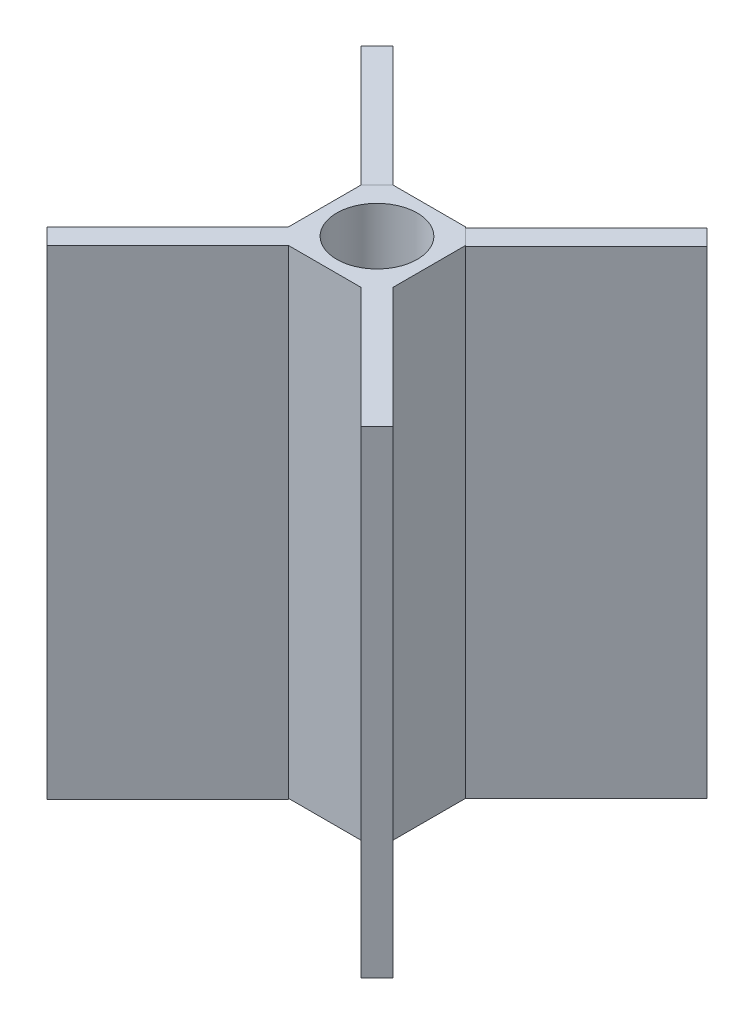
SolidWorks part; units mm, degrees
ref_plane "Front Plane" through (0, 0, 0) normal (0, 0, 1) x (1, 0, 0)
ref_plane "Top Plane" through (0, 0, 0) normal (0, 1, 0) x (1, 0, 0)
ref_plane "Right Plane" through (0, 0, 0) normal (1, 0, 0) x (0, 0, -1)
sketch "Sketch1" plane through (0, 0, 0) normal (0, 1, 0) x (1, 0, 0)
  line L1 (-6.5, -6.5) -> (6.5, -6.5)
  line L2 (-6.5, -6.5) -> (-6.5, 6.5)
  line L3 (-6.5, 6.5) -> (6.5, 6.5)
  line L4 (6.5, -6.5) -> (6.5, 6.5)
  line L5 (-6.5, -6.5) -> (6.5, 6.5) construction
  line L6 (-6.5, 6.5) -> (6.5, -6.5) construction
  point P0 (0, 0)
  dimension "D1" = 13
  dimension "D2" = 13
extrude "Boss-Extrude1" add sketch "Sketch1" along normal blind 59.5
chamfer "Chamfer1" distance 2 angle 45 4 edges at (-6.5, 29.75, 6.5) (6.5, 29.75, 6.5) (6.5, 29.75, -6.5) (-6.5, 29.75, -6.5)
sketch "Sketch6" plane through (5.5, 0, -5.5) normal (0.7071, 0, -0.7071) x (-0.7071, 0, -0.7071)
  line L0 (-1.4142, 0) -> (1.4142, 0)
  line L1 (-1.4142, 0) -> (-1.4142, 59.3706)
  line L2 (1.4142, 0) -> (1.4142, 59.3706)
  line L3 (-1.4142, 59.3706) -> (1.4142, 59.3706)
extrude "Boss-Extrude3" add sketch "Sketch6" along normal blind 21.22
sketch "Sketch5" plane through (-5.5, 0, -5.5) normal (-0.7071, 0, -0.7071) x (-0.7071, 0, 0.7071)
  line L0 (-1.4142, 0) -> (1.4142, 0)
  line L1 (-1.4142, 0) -> (-1.4142, 59.4605)
  line L2 (1.4142, 0) -> (1.4142, 59.4605)
  line L3 (-1.4142, 59.4605) -> (1.4142, 59.4605)
extrude "Boss-Extrude2" add sketch "Sketch5" along normal blind 21.22
sketch "Sketch7" plane through (-5.5, 0, 5.5) normal (-0.7071, 0, 0.7071) x (0.7071, 0, 0.7071)
  line L0 (1.4142, 59.5) -> (-1.4142, 59.5)
  line L1 (1.4142, 59.5) -> (1.4142, -0.1143)
  line L2 (-1.4142, 59.5) -> (-1.4142, -0.1143)
  line L3 (1.4142, -0.1143) -> (-1.4142, -0.1143)
extrude "Boss-Extrude4" add sketch "Sketch7" along normal blind 21.22
sketch "Sketch8" plane through (5.5, 0, 5.5) normal (0.7071, 0, 0.7071) x (0.7071, 0, -0.7071)
  line L0 (1.4142, 59.5) -> (-1.4142, 59.5)
  line L1 (1.4142, 59.5) -> (1.4142, 0.1742)
  line L2 (-1.4142, 59.5) -> (-1.4142, 0.1742)
  line L3 (1.4142, 0.1742) -> (-1.4142, 0.1742)
extrude "Boss-Extrude5" add sketch "Sketch8" along normal blind 21.22
sketch "Sketch10" plane through (0, 59.5, 0) normal (0, 1, 0) x (1, 0, 0)
  circle A0 centre (0, 0) radius 5
  dimension "D1" = 10
extrude "Cut-Extrude2" cut sketch "Sketch10" against normal through all
